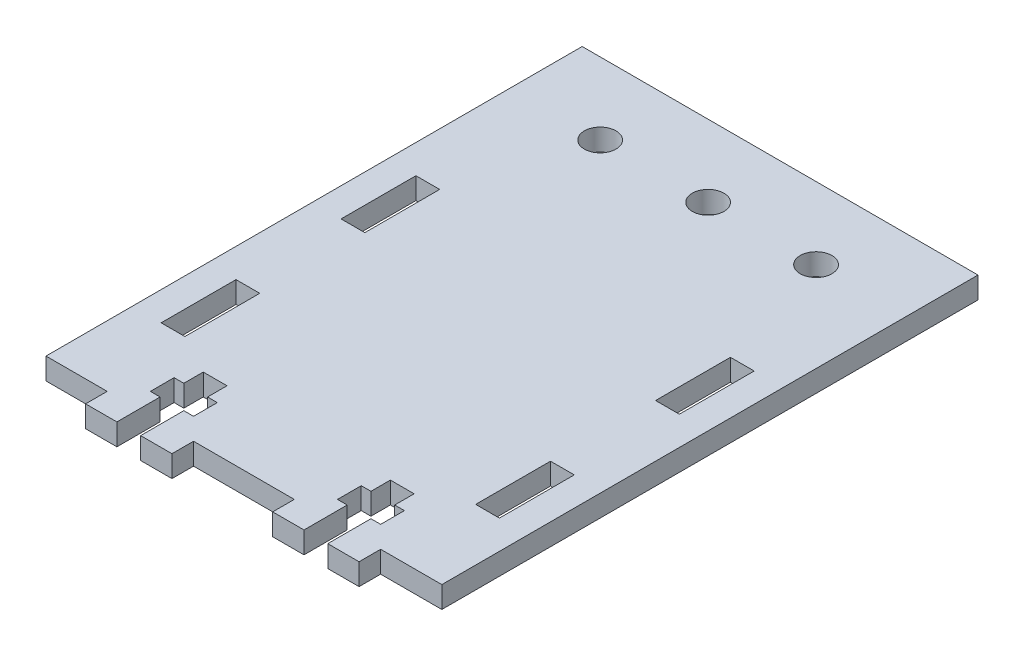
SolidWorks part; units mm, degrees
material "Thornel Mat VMA"
ref_plane "前视基准面" through (0, 0, 0) normal (0, 0, 1) x (1, 0, 0)
ref_plane "上视基准面" through (0, 0, 0) normal (0, 1, 0) x (1, 0, 0)
ref_plane "右视基准面" through (0, 0, 0) normal (1, 0, 0) x (0, 0, -1)
other "Configuration Table"
sketch "草图1" plane through (0, 0, 0) normal (0, 1, 0) x (1, 0, 0)
  line L0 (0, -6.5537) -> (0, -30.8889) construction
  line L1 (-27.5, 37.25) -> (27.5, 37.25)
  line L2 (-27.5, 37.25) -> (-27.5, -37.25)
  line L3 (-27.5, -37.25) -> (27.5, -37.25)
  line L4 (27.5, 37.25) -> (27.5, -37.25)
  line L5 (-27.5, 37.25) -> (27.5, -37.25) construction
  line L6 (-27.5, -37.25) -> (27.5, 37.25) construction
  line L7 (-19, -37.25) -> (-7, -37.25)
  line L8 (-19, -37.25) -> (-19, -40.25)
  line L9 (-19, -40.25) -> (-7, -40.25)
  line L10 (-7, -37.25) -> (-7, -40.25)
  line L11 (19, -40.25) -> (7, -40.25)
  line L12 (-27.5, 37.25) -> (27.5, 37.25) construction
  line L13 (-27.5, 37.25) -> (-27.5, 27.25) construction
  line L14 (-27.5, 27.25) -> (27.5, 27.25) construction
  line L15 (27.5, 37.25) -> (27.5, 27.25) construction
  line L16 (7, -37.25) -> (7, -40.25)
  line L17 (19, -37.25) -> (7, -37.25)
  line L18 (19, -37.25) -> (19, -40.25)
  circle A0 centre (0, 27.25) radius 2.2
  circle A1 centre (-15, 27.25) radius 2.2
  circle A2 centre (15, 27.25) radius 2.2
  point P0 (0, 0)
  dimension "D7" = 4.4
  dimension "D8" = 15
  dimension "D1" = 55
  dimension "D2" = 74.5
  dimension "D3" = 3
  dimension "D4" = 12
  dimension "D5" = 7
  dimension "D6" = 10
extrude "凸台-拉伸1" add sketch "草图1" along normal blind 3 contours L4 L1 L2 L3 A0 A1 A2 | L10 L3 L8 L9 | L18 L3 L16 L11
sketch "草图2" plane through (0, 3, 0) normal (0, 1, 0) x (1, 0, 0)
  line L0 (-27.5, 37.25) -> (-27.5, -37.25) construction
  line L1 (-23.5, -14.85) -> (-20.2, -14.85)
  line L2 (-23.5, -14.85) -> (-23.5, -25.25)
  line L3 (-23.5, -25.25) -> (-20.2, -25.25)
  line L4 (-20.2, -14.85) -> (-20.2, -25.25)
  line L5 (-27.5, -37.25) -> (-19, -37.25) construction
  line L6 (0, 6.2279) -> (0, -5.2551) construction
  line L7 (23.5, -25.25) -> (20.2, -25.25)
  line L8 (20.2, -14.85) -> (20.2, -25.25)
  line L9 (23.5, -14.85) -> (20.2, -14.85)
  line L10 (23.5, -14.85) -> (23.5, -25.25)
  dimension "D1" = 3.3
  dimension "D2" = 10.4
  dimension "D3" = 4
  dimension "D4" = 12
extrude "切除-拉伸1" cut sketch "草图2" against normal blind 3
sketch "草图3" plane through (0, 3, 0) normal (0, 1, 0) x (1, 0, 0)
  line L0 (-19, -40.25) -> (-7, -40.25) construction
  line L1 (-14.65, -28.25) -> (-11.35, -28.25)
  line L2 (-14.65, -28.25) -> (-14.65, -52.25)
  line L3 (-14.65, -52.25) -> (-11.35, -52.25)
  line L4 (-11.35, -28.25) -> (-11.35, -52.25)
  line L5 (-14.65, -28.25) -> (-11.35, -52.25) construction
  line L6 (-14.65, -52.25) -> (-11.35, -28.25) construction
  line L7 (-13, -40.25) -> (-13, -32.6) construction
  line L8 (0, -8.5477) -> (0, -32.2747) construction
  line L9 (-16, -30.95) -> (-10, -30.95)
  line L10 (-16, -30.95) -> (-16, -34.25)
  line L11 (-16, -34.25) -> (-10, -34.25)
  line L12 (-10, -30.95) -> (-10, -34.25)
  line L13 (-16, -30.95) -> (-10, -34.25) construction
  line L14 (-16, -34.25) -> (-10, -30.95) construction
  line L15 (16, -34.25) -> (10, -30.95) construction
  line L16 (16, -30.95) -> (10, -34.25) construction
  line L17 (13, -40.25) -> (13, -32.6) construction
  line L18 (14.65, -52.25) -> (11.35, -28.25) construction
  line L19 (14.65, -28.25) -> (11.35, -52.25) construction
  line L20 (10, -30.95) -> (10, -34.25)
  line L21 (16, -34.25) -> (10, -34.25)
  line L22 (16, -30.95) -> (16, -34.25)
  line L23 (16, -30.95) -> (10, -30.95)
  line L24 (11.35, -28.25) -> (11.35, -52.25)
  line L25 (14.65, -52.25) -> (11.35, -52.25)
  line L26 (14.65, -28.25) -> (14.65, -52.25)
  line L27 (14.65, -28.25) -> (11.35, -28.25)
  point P0 (-13, -40.25)
  point P26 (13, -40.25)
  point P27 (0, 0)
  line M16 (-19, -40.25) -> (-7, -40.25)
  line M20 (7, -40.25) -> (19, -40.25)
  dimension "D1" = 3.3
  dimension "D2" = 24
  dimension "D3" = 3.3
  dimension "D4" = 6
  dimension "D5" = 6
extrude "切除-拉伸2" cut sketch "草图3" against normal blind 3 contours L12 L9 L4 L11 | L2 L9 L4 L1 | L2 L11 L4 L9 | L11 L2 L4 M16 | L10 L11 L2 L9 | L26 L21 L24 M20 | L23 L26 L21 L22 | L26 L23 L24 L21 | L26 L27 L24 L23 | L24 L23 L20 L21
pattern_linear "阵列(线性)1" count 2 spacing 25 along (0, 0, -1) of "切除-拉伸1"
